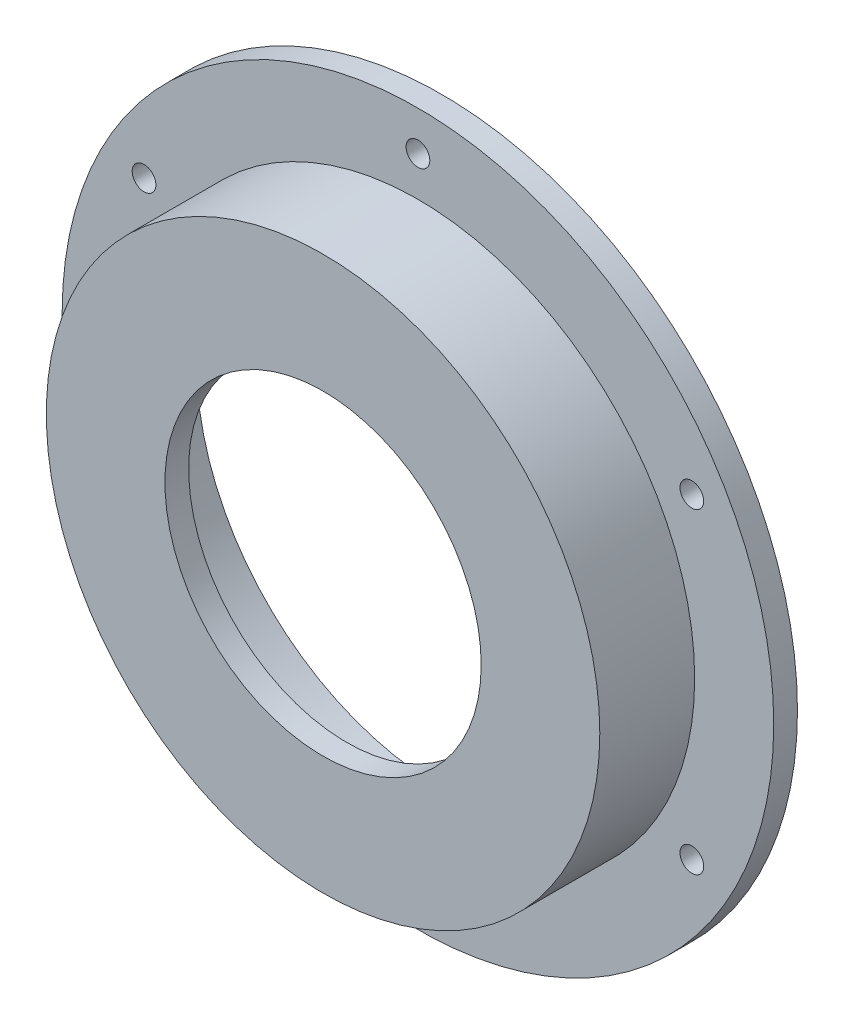
SolidWorks part; units mm, degrees
ref_plane "Front Plane" through (0, 0, 0) normal (0, 0, 1) x (1, 0, 0)
ref_plane "Top Plane" through (0, 0, 0) normal (0, 1, 0) x (1, 0, 0)
ref_plane "Right Plane" through (0, 0, 0) normal (1, 0, 0) x (0, 0, -1)
sketch "Sketch1" plane through (0, 0, 0) normal (0, 0, 1) x (1, 0, 0)
  circle A0 centre (0, 0) radius 45
  dimension "D1" = 90
extrude "Boss-Extrude3" add sketch "Sketch1" along normal blind 3
sketch "Sketch2" plane through (0, 0, 3) normal (0, 0, 1) x (1, 0, 0)
  circle A0 centre (0, 0) radius 35
  dimension "D1" = 70
extrude "Boss-Extrude4" add sketch "Sketch2" along normal blind 12
sketch "Sketch3" plane through (0, 0, 15) normal (0, 0, 1) x (1, 0, 0)
  circle A0 centre (0, 0) radius 31
  dimension "D1" = 62
extrude "Cut-Extrude2" cut sketch "Sketch3" against normal through all
sketch "Sketch4" plane through (0, 0, 15) normal (0, 0, 1) x (1, 0, 0)
  circle A0 centre (0, 0) radius 35
  circle A1 centre (0, 0) radius 20
  dimension "D1" = 40
extrude "Boss-Extrude5" add sketch "Sketch4" against normal blind 3
sketch "Sketch5" plane through (0, 0, 3) normal (0, 0, 1) x (1, 0, 0)
  circle A0 centre (0, 40) radius 1.5
  circle A1 centre (0, 0) radius 40 construction
  circle A2 centre (34.641, 20) radius 1.5
  circle A3 centre (34.641, -20) radius 1.5
  circle A4 centre (0, -40) radius 1.5
  circle A5 centre (-34.641, -20) radius 1.5
  circle A6 centre (-34.641, 20) radius 1.5
  point P18 (0, 0)
  dimension "D1" = 80
  dimension "D2" = 3
  dimension "D3" = 6
extrude "Cut-Extrude3" cut sketch "Sketch5" against normal through all and the other way through all
